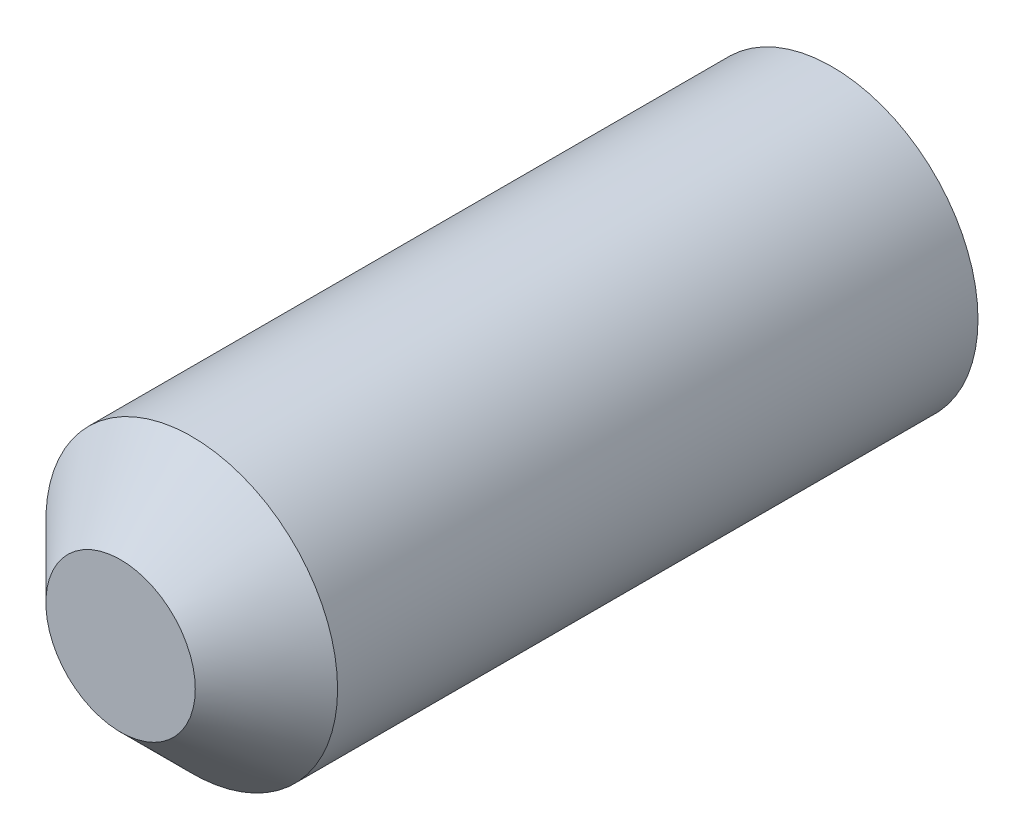
SolidWorks part; units mm, degrees
ref_plane "Piano frontale" through (0, 0, 0) normal (0, 0, 1) x (1, 0, 0)
ref_plane "Piano superiore" through (0, 0, 0) normal (0, 1, 0) x (1, 0, 0)
ref_plane "Piano destro" through (0, 0, 0) normal (1, 0, 0) x (0, 0, -1)
sketch "Schizzo1" plane through (0, 0, 0) normal (0, 0, 1) x (1, 0, 0)
  circle A0 centre (0, 0) radius 2.05
  dimension "D1" = 4.1
extrude "Estrusione-Estrusione1" add sketch "Schizzo1" along normal blind 10
chamfer "Smusso1" distance 1 angle 45 1 edges at (2.05, 0, 10)
